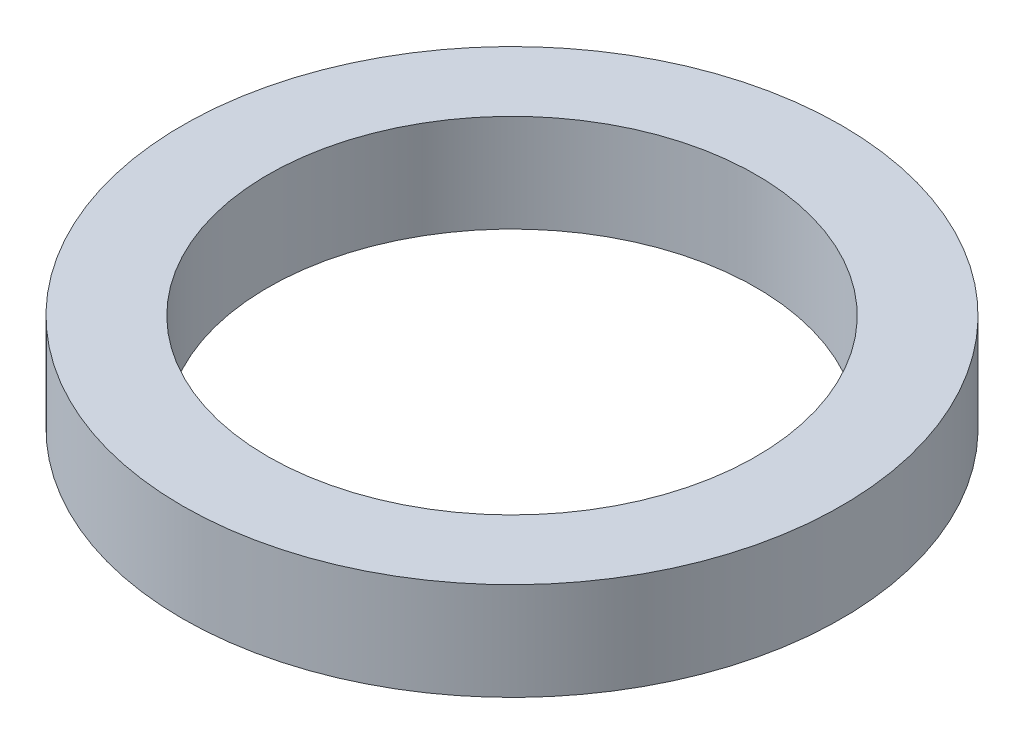
SolidWorks part; units mm, degrees
ref_plane "前视基准面" through (0, 0, 0) normal (0, 0, 1) x (1, 0, 0)
ref_plane "上视基准面" through (0, 0, 0) normal (0, 1, 0) x (1, 0, 0)
ref_plane "右视基准面" through (0, 0, 0) normal (1, 0, 0) x (0, 0, -1)
sketch "草图1" plane through (0, 0, 0) normal (0, 1, 0) x (1, 0, 0)
  circle A0 centre (0, 0) radius 10
  circle A1 centre (0, 0) radius 13.5
  dimension "D1" = 20
  dimension "D2" = 27
extrude "凸台-拉伸1" add sketch "草图1" along normal blind 4
